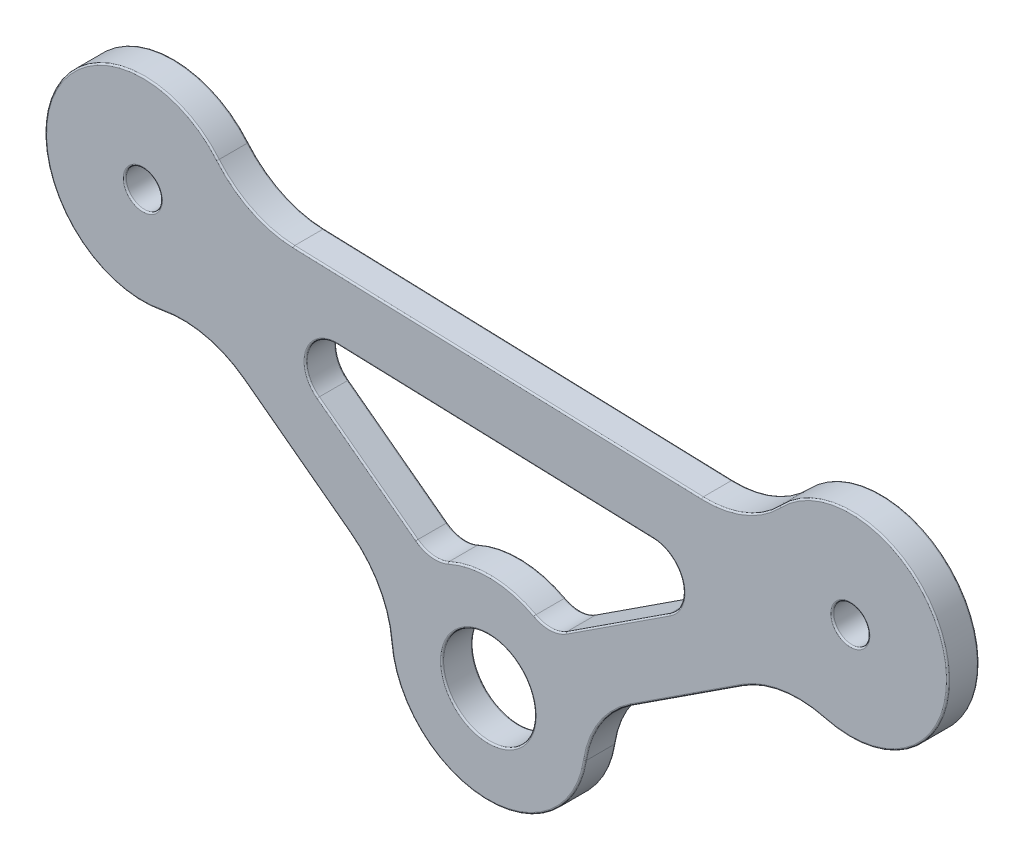
SolidWorks part; units mm, degrees
material "Plain Carbon Steel"
ref_plane "Front Plane" through (0, 0, 0) normal (0, 0, 1) x (1, 0, 0)
ref_plane "Top Plane" through (0, 0, 0) normal (0, 1, 0) x (1, 0, 0)
ref_plane "Right Plane" through (0, 0, 0) normal (1, 0, 0) x (0, 0, -1)
sketch "Sketch1" plane through (0, 0, 0) normal (0, 0, 1) x (1, 0, 0)
  line L0 (16.9381, 131.648) -> (52.1117, 154.5962) construction
  line L1 (52.1117, 154.5962) -> (-16.6441, 156.8502) construction
  line L2 (-16.6441, 156.8502) -> (16.9381, 131.648) construction
  line L3 (16.9381, 131.648) -> (52.1117, 154.5962) construction
  line L4 (52.1117, 154.5962) -> (-16.6441, 156.8502) construction
  line L5 (-16.6441, 156.8502) -> (16.9381, 131.648) construction
  circle A0 centre (16.9381, 131.648) radius 4.5
  circle A1 centre (16.9381, 131.648) radius 9.5
  circle A2 centre (52.1117, 154.5962) radius 1.75
  circle A3 centre (52.1117, 154.5962) radius 9.5
  circle A4 centre (-16.6441, 156.8502) radius 9.5
  circle A5 centre (-16.6441, 156.8502) radius 1.75
  dimension "D1" = 19
  dimension "D2" = 3.5
  dimension "D3" = 9
extrude "Boss-Extrude1" add sketch "Sketch1" along normal blind 3
sketch "Sketch2" plane through (0, 0, 3) normal (0, 0, 1) x (1, 0, 0)
  line L0 (45.219, 154.8222) -> (-9.7514, 156.6242)
  line L1 (52.1117, 154.5962) -> (-16.6441, 156.8502) construction
  line L2 (12.1443, 135.2455) -> (-11.8503, 153.2526)
  line L3 (-16.6441, 156.8502) -> (16.9381, 131.648) construction
  line L4 (21.9622, 134.9259) -> (47.0876, 151.3184)
  line L5 (16.9381, 131.648) -> (52.1117, 154.5962) construction
  point P5 (17.7338, 155.7232)
  point P10 (0.147, 144.2491)
  point P15 (34.5249, 143.1221)
  point P16 (17.7338, 155.7232)
  dimension "D1" = 55
  dimension "D2" = 30
extrude "Extrude-Thin1" add sketch "Sketch2" against normal blind 3 thin thin type mid plane wall 6
fillet "Fillet1" radius 3 4 edges at (22.8481, 139.0859, 1.5) (11.5293, 139.4579, 1.5) (42.5035, 151.9096, 1.5) (-7.2354, 153.5402, 1.5)
fillet "Fillet2" radius 10 6 edges at (43.201, 157.89, 1.5) (46.2017, 147.1583, 1.5) (26.1266, 134.0608, 1.5) (7.9279, 134.659, 1.5) (-11.2353, 149.0403, 1.5) (-7.5368, 159.5533, 1.5)
fillet "Fillet3" radius 0.15 46 edges at (53.8617, 154.5962, 0) (-14.8941, 156.8502, 0) (21.4381, 131.648, 0) (45.4734, 145.6428, 0) (61.2608, 157.1545, 0) (41.7922, 158.8079, 0) (17.8321, 158.7216, 3) (17.8321, 158.7216, 0) (-6.0709, 160.377, 0) (-25.6057, 160.003, 0) (-10.6081, 147.4802, 0) (-1.6537, 141.8496, 0) (-1.6537, 141.8496, 3) (6.2547, 134.8253, 0) (16.626, 122.1531, 0) (27.8071, 134.1169, 0) (36.1642, 140.6096, 0) (36.1642, 140.6096, 3) (11.4433, 140.0467, 0) (5.1703, 144.2301, 3) (5.1703, 144.2301, 0) (-0.6567, 151.2257, 0) (17.6326, 152.7249, 0) (17.6326, 152.7249, 3) (35.7845, 150.0308, 0) (29.5087, 143.4314, 0) (29.5087, 143.4314, 3) (22.9727, 139.6678, 0) (17.2502, 141.1429, 0) (53.8617, 154.5962, 3) (-14.8941, 156.8502, 3) (21.4381, 131.648, 3) (-10.6081, 147.4802, 3) (-25.6057, 160.003, 3) (-6.0709, 160.377, 3) (41.7922, 158.8079, 3) (61.2608, 157.1545, 3) (45.4734, 145.6428, 3) (27.8071, 134.1169, 3) (16.626, 122.1531, 3) (6.2547, 134.8253, 3) (-0.6567, 151.2257, 3) (11.4433, 140.0467, 3) (17.2502, 141.1429, 3) (22.9727, 139.6678, 3) (35.7845, 150.0308, 3)
